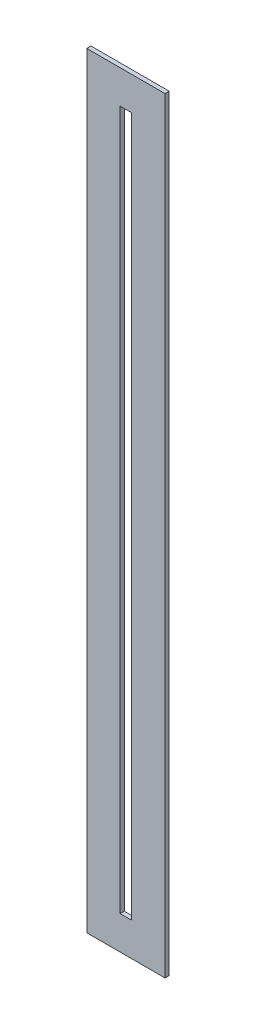
SolidWorks part; units mm, degrees
ref_plane "Front" through (0, 0, 0) normal (0, 0, 1) x (1, 0, 0)
ref_plane "Top" through (0, 0, 0) normal (0, 1, 0) x (1, 0, 0)
ref_plane "Right" through (0, 0, 0) normal (1, 0, 0) x (0, 0, -1)
sketch "Sketch1" plane through (0, 0, 0) normal (0, 0, 1) x (1, 0, 0)
  line L1 (0, 0) -> (8.89, 0)
  line L2 (0, 0) -> (0, 533.4)
  line L3 (0, 533.4) -> (8.89, 533.4)
  line L4 (8.89, 0) -> (8.89, 533.4)
  line L5 (34.29, -25.4) -> (-25.4, -25.4)
  line L6 (34.29, -25.4) -> (34.29, 558.8)
  line L7 (34.29, 558.8) -> (-25.4, 558.8)
  line L8 (-25.4, -25.4) -> (-25.4, 558.8)
  line L9 (34.29, -25.4) -> (-25.4, 558.8) construction
  line L10 (34.29, 558.8) -> (-25.4, -25.4) construction
  point P5 (4.445, 266.7)
  dimension "D1" = 533.4
  dimension "D2" = 8.89
  dimension "D3" = 25.4
  dimension "D4" = 25.4
  dimension "D5" = 25.4
  dimension "D6" = 25.4
extrude "Boss-Extrude1" add sketch "Sketch1" along normal blind 3.175
